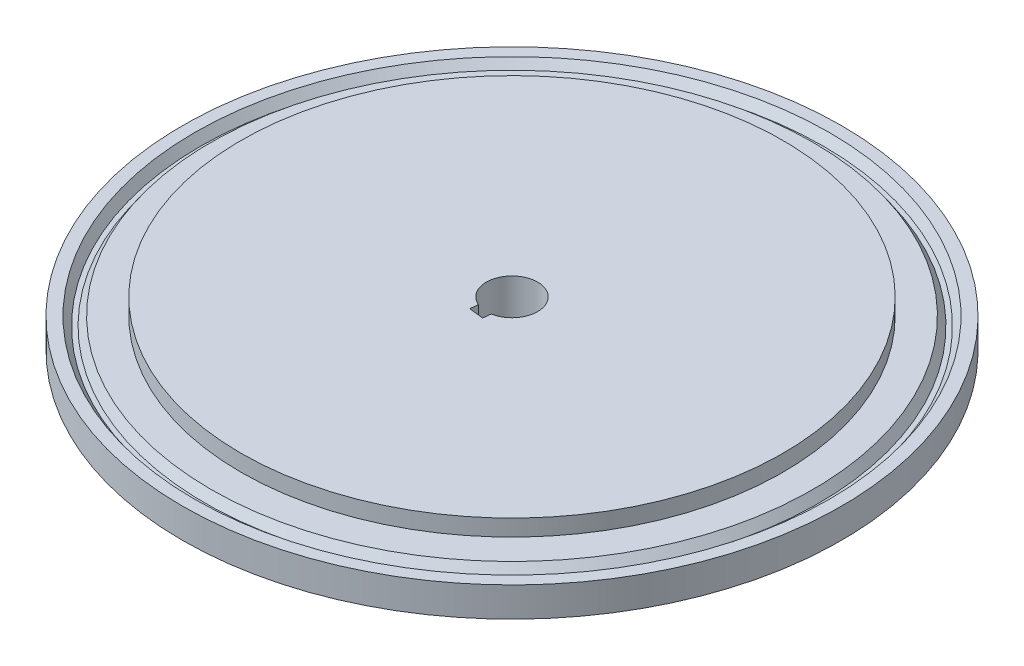
SolidWorks part; units mm, degrees
ref_plane "Спереди" through (0, 0, 0) normal (0, 0, 1) x (1, 0, 0)
ref_plane "Сверху" through (0, 0, 0) normal (0, 1, 0) x (1, 0, 0)
ref_plane "Справа" through (0, 0, 0) normal (1, 0, 0) x (0, 0, -1)
sketch "Эскиз1" plane through (0, 0, 0) normal (0, 1, 0) x (1, 0, 0)
  circle A0 centre (0, 0) radius 90
extrude "Вытянуть1" add sketch "Эскиз1" along normal blind 12.6
sketch "Эскиз3" plane through (0, 0, 0) normal (0, -1, 0) x (1, 0, 0)
  line L0 (-2.7411, 6.441) -> (-2.9818, 8.5692)
  line L1 (-2.9818, 8.5692) -> (0.9929, 9.0187)
  line L2 (0.9929, 9.0187) -> (1.2336, 6.8905)
  arc A0 (-2.7411, 6.441) -> (1.2336, 6.8905) centre (0, 0) ccw
extrude "Вырез-Вытянуть2" cut sketch "Эскиз3" against normal blind 32
sketch "Эскиз4" plane through (0, 0, 0) normal (0, 0, 1) x (1, 0, 0)
  line L0 (0, 80) -> (0, 102.8113) construction
  line L1 (68.8639, 5.4784) -> (72.4006, 5.4784)
  line L2 (68.8639, 5.4784) -> (63.3677, -0.2678)
  line L3 (63.3677, -0.2678) -> (77.8967, -0.2678)
  line L5 (72.4006, 5.4784) -> (77.8967, -0.2678)
revolve "Вырез-Повернуть1" cut sketch "Эскиз4" angle 360 about L0
sketch "Эскиз7" plane through (0, 0, 0) normal (0, 0, 1) x (1, 0, 0)
  line L0 (0, 0) -> (0, 108.9443) construction
  line L1 (85.0628, 5.7004) -> (87.6171, 9.4231)
  line L2 (87.6171, 9.4231) -> (81.2487, 9.4231)
  line L3 (81.2487, 9.4231) -> (83.8029, 5.7004)
  line L4 (84.4329, 9.4231) -> (84.4329, 10.1724) construction
  line L5 (83.8029, 5.7004) -> (85.0628, 5.7004)
revolve "Вырез-Повернуть2" cut sketch "Эскиз7" angle 360 about L0
sketch "Эскиз12" plane through (0, 12.6, 0) normal (0, 1, 0) x (1, 0, 0)
  circle A0 centre (0, 0) radius 90.5
  circle A1 centre (0, 0) radius 74
extrude "Вытянуть3" cut sketch "Эскиз12" against normal blind 4.5
